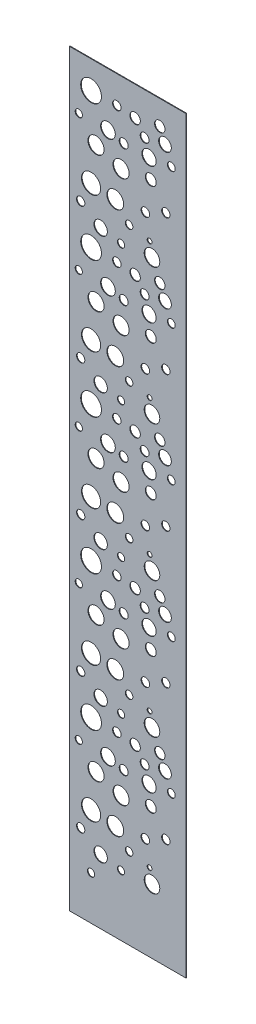
SolidWorks part; units mm, degrees
ref_plane "Front Plane" through (0, 0, 0) normal (0, 0, 1) x (1, 0, 0)
ref_plane "Top Plane" through (0, 0, 0) normal (0, 1, 0) x (1, 0, 0)
ref_plane "Right Plane" through (0, 0, 0) normal (1, 0, 0) x (0, 0, -1)
sketch "Sketch1" plane through (0, 0, 0) normal (0, 0, 1) x (1, 0, 0)
  line L39 (0, 0) -> (609.6, 0)
  line L40 (0, 0) -> (0, 3924.3)
  line L41 (0, 3924.3) -> (609.6, 3924.3)
  line L42 (609.6, 0) -> (609.6, 3924.3)
  circle A17 centre (112.851, 3779.6748) radius 54.3982
  circle A18 centre (247.7954, 3779.6748) radius 22.1743
  circle A19 centre (343.6934, 3769.978) radius 27.2981
  circle A20 centre (393.5041, 3706.1687) radius 23.2273
  circle A21 centre (416.7313, 3628.4625) radius 37.1736
  circle A22 centre (425.8604, 3531.9627) radius 28.5909
  circle A23 centre (269.9697, 3503.3718) radius 42.2062
  circle A24 centre (201.285, 3644.5795) radius 38.487
  circle A25 centre (138.8034, 3545.5779) radius 42.2062
  circle A26 centre (112.851, 3359.4195) radius 50.1801
  circle A27 centre (239.7719, 3349.5477) radius 43.9756
  circle A28 centre (397.2695, 3370.2535) radius 22.2741
  circle A29 centre (504.7035, 3421.2354) radius 21.8181
  circle A30 centre (269.9697, 3163.3473) radius 18.7516
  circle A31 centre (163.0312, 3182.0989) radius 35.129
  circle A32 centre (312.1759, 3270.1984) radius 19.7335
  circle A33 centre (419.5436, 3250.465) radius 12.5778
  circle A34 centre (432.1214, 3182.0989) radius 40.8356
  circle A36 centre (58.4529, 3250.465) radius 21.7181
  circle A37 centre (48.5241, 3644.5795) radius 18.9298
  circle A38 centre (472.957, 3797.2761) radius 27.2981
  circle A39 centre (500.2551, 3729.3959) radius 33.2552
  circle A40 centre (533.5103, 3644.5795) radius 20.4299
  circle A41 centre (283.7475, 3625.6497) radius 23.4638
  circle A42 centre (112.851, 3068.4748) radius 54.3982
  circle A43 centre (247.7954, 3068.4748) radius 22.1743
  circle A44 centre (343.6934, 3058.778) radius 27.2981
  circle A45 centre (393.5041, 2994.9687) radius 23.2273
  circle A46 centre (416.7313, 2917.2625) radius 37.1736
  circle A47 centre (425.8604, 2820.7627) radius 28.5909
  circle A48 centre (269.9697, 2792.1718) radius 42.2062
  circle A49 centre (201.285, 2933.3795) radius 38.487
  circle A50 centre (138.8034, 2834.3779) radius 42.2062
  circle A51 centre (112.851, 2648.2195) radius 50.1801
  circle A52 centre (239.7719, 2638.3477) radius 43.9756
  circle A53 centre (397.2695, 2659.0535) radius 22.2741
  circle A54 centre (504.7035, 2710.0354) radius 21.8181
  circle A55 centre (269.9697, 2452.1473) radius 18.7516
  circle A56 centre (163.0312, 2470.8989) radius 35.129
  circle A57 centre (312.1759, 2558.9984) radius 19.7335
  circle A58 centre (419.5436, 2539.265) radius 12.5778
  circle A59 centre (432.1214, 2470.8989) radius 40.8356
  circle A61 centre (58.4529, 2539.265) radius 21.7181
  circle A62 centre (48.5241, 2933.3795) radius 18.9298
  circle A63 centre (472.957, 3086.0761) radius 27.2981
  circle A64 centre (500.2551, 3018.1959) radius 33.2552
  circle A65 centre (533.5103, 2933.3795) radius 20.4299
  circle A66 centre (283.7475, 2914.4497) radius 23.4638
  circle A67 centre (112.851, 2357.2748) radius 54.3982
  circle A68 centre (247.7954, 2357.2748) radius 22.1743
  circle A69 centre (343.6934, 2347.578) radius 27.2981
  circle A70 centre (393.5041, 2283.7687) radius 23.2273
  circle A71 centre (416.7313, 2206.0625) radius 37.1736
  circle A72 centre (425.8604, 2109.5627) radius 28.5909
  circle A73 centre (269.9697, 2080.9718) radius 42.2062
  circle A74 centre (201.285, 2222.1795) radius 38.487
  circle A75 centre (138.8034, 2123.1779) radius 42.2062
  circle A76 centre (112.851, 1937.0195) radius 50.1801
  circle A77 centre (239.7719, 1927.1477) radius 43.9756
  circle A78 centre (397.2695, 1947.8535) radius 22.2741
  circle A79 centre (504.7035, 1998.8354) radius 21.8181
  circle A80 centre (269.9697, 1740.9473) radius 18.7516
  circle A81 centre (163.0312, 1759.6989) radius 35.129
  circle A82 centre (312.1759, 1847.7984) radius 19.7335
  circle A83 centre (419.5436, 1828.065) radius 12.5778
  circle A84 centre (432.1214, 1759.6989) radius 40.8356
  circle A86 centre (58.4529, 1828.065) radius 21.7181
  circle A87 centre (48.5241, 2222.1795) radius 18.9298
  circle A88 centre (472.957, 2374.8761) radius 27.2981
  circle A89 centre (500.2551, 2306.9959) radius 33.2552
  circle A90 centre (533.5103, 2222.1795) radius 20.4299
  circle A91 centre (283.7475, 2203.2497) radius 23.4638
  circle A92 centre (112.851, 1646.0748) radius 54.3982
  circle A93 centre (247.7954, 1646.0748) radius 22.1743
  circle A94 centre (343.6934, 1636.378) radius 27.2981
  circle A95 centre (393.5041, 1572.5687) radius 23.2273
  circle A96 centre (416.7313, 1494.8625) radius 37.1736
  circle A97 centre (425.8604, 1398.3627) radius 28.5909
  circle A98 centre (269.9697, 1369.7718) radius 42.2062
  circle A99 centre (201.285, 1510.9795) radius 38.487
  circle A100 centre (138.8034, 1411.9779) radius 42.2062
  circle A101 centre (112.851, 1225.8195) radius 50.1801
  circle A102 centre (239.7719, 1215.9477) radius 43.9756
  circle A103 centre (397.2695, 1236.6535) radius 22.2741
  circle A104 centre (504.7035, 1287.6354) radius 21.8181
  circle A105 centre (269.9697, 1029.7473) radius 18.7516
  circle A106 centre (163.0312, 1048.4989) radius 35.129
  circle A107 centre (312.1759, 1136.5984) radius 19.7335
  circle A108 centre (419.5436, 1116.865) radius 12.5778
  circle A109 centre (432.1214, 1048.4989) radius 40.8356
  circle A111 centre (58.4529, 1116.865) radius 21.7181
  circle A112 centre (48.5241, 1510.9795) radius 18.9298
  circle A113 centre (472.957, 1663.6761) radius 27.2981
  circle A114 centre (500.2551, 1595.7959) radius 33.2552
  circle A115 centre (533.5103, 1510.9795) radius 20.4299
  circle A116 centre (283.7475, 1492.0497) radius 23.4638
  circle A117 centre (112.851, 934.8748) radius 54.3982
  circle A118 centre (247.7954, 934.8748) radius 22.1743
  circle A119 centre (343.6934, 925.178) radius 27.2981
  circle A120 centre (393.5041, 861.3687) radius 23.2273
  circle A121 centre (416.7313, 783.6625) radius 37.1736
  circle A122 centre (425.8604, 687.1627) radius 28.5909
  circle A123 centre (269.9697, 658.5718) radius 42.2062
  circle A124 centre (201.285, 799.7795) radius 38.487
  circle A125 centre (138.8034, 700.7779) radius 42.2062
  circle A126 centre (112.851, 514.6195) radius 50.1801
  circle A127 centre (239.7719, 504.7477) radius 43.9756
  circle A128 centre (397.2695, 525.4535) radius 22.2741
  circle A129 centre (504.7035, 576.4354) radius 21.8181
  circle A130 centre (269.9697, 318.5473) radius 18.7516
  circle A131 centre (163.0312, 337.2989) radius 35.129
  circle A132 centre (312.1759, 425.3984) radius 19.7335
  circle A133 centre (419.5436, 405.665) radius 12.5778
  circle A134 centre (432.1214, 337.2989) radius 40.8356
  circle A135 centre (112.851, 229.5927) radius 19.0649
  circle A136 centre (58.4529, 405.665) radius 21.7181
  circle A137 centre (48.5241, 799.7795) radius 18.9298
  circle A138 centre (472.957, 952.4761) radius 27.2981
  circle A139 centre (500.2551, 884.5959) radius 33.2552
  circle A140 centre (533.5103, 799.7795) radius 20.4299
  circle A141 centre (283.7475, 780.8497) radius 23.4638
  dimension "D1" = 609.6
  dimension "D2" = 3924.3
  dimension "D3" = 5
extrude "Boss-Extrude1" add sketch "Sketch1" along normal blind 3.175
